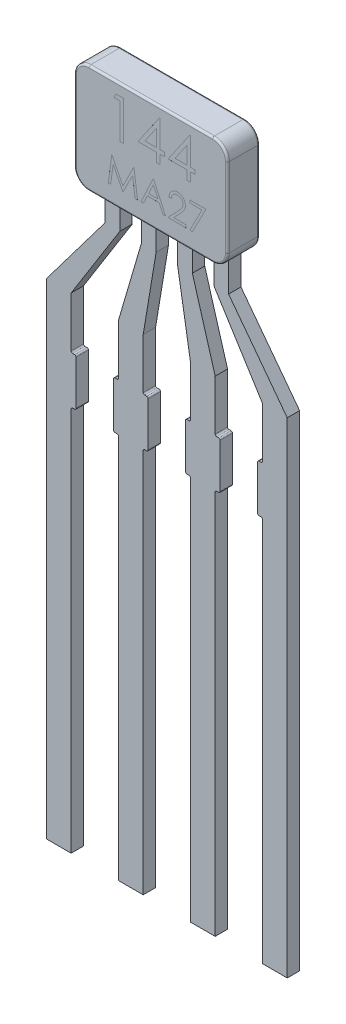
SolidWorks part; units mm, degrees
ref_plane "Front Plane" through (0, 0, 0) normal (0, 0, 1) x (1, 0, 0)
ref_plane "Top Plane" through (0, 0, 0) normal (0, 1, 0) x (1, 0, 0)
ref_plane "Right Plane" through (0, 0, 0) normal (1, 0, 0) x (0, 0, -1)
sketch "Sketch1" plane through (0, 0, 0) normal (0, 0, 1) x (1, 0, 0)
  line L1 (-1.25, 1.1) -> (1.25, 1.1)
  line L2 (-1.55, 0.8) -> (-1.55, -0.8)
  line L3 (-1.25, -1.1) -> (1.25, -1.1)
  line L4 (1.55, 0.8) -> (1.55, -0.8)
  line L5 (-1.55, 1.1) -> (1.55, -1.1) construction
  line L6 (-1.55, -1.1) -> (1.55, 1.1) construction
  arc A0 (-1.55, -0.8) -> (-1.25, -1.1) centre (-1.25, -0.8) ccw
  arc A1 (1.25, -1.1) -> (1.55, -0.8) centre (1.25, -0.8) ccw
  arc A2 (1.55, 0.8) -> (1.25, 1.1) centre (1.25, 0.8) ccw
  arc A3 (-1.25, 1.1) -> (-1.55, 0.8) centre (-1.25, 0.8) ccw
  point P0 (0, 0)
  dimension "D3" = 0.3
  dimension "D1" = 3.1
  dimension "D2" = 2.2
extrude "Boss-Extrude1" add sketch "Sketch1" along normal mid plane 0.65
fillet "Fillet1" radius 0.04 16 edges at (1.4621, -1.0121, -0.325) (0, -1.1, -0.325) (-1.4621, -1.0121, -0.325) (-1.55, 0, -0.325) (-1.4621, 1.0121, -0.325) (0, 1.1, -0.325) (1.4621, 1.0121, -0.325) (1.4621, 1.0121, 0.325) (1.55, 0, 0.325) (1.4621, -1.0121, 0.325) (0, -1.1, 0.325) (-1.4621, -1.0121, 0.325) (-1.55, 0, 0.325) (-1.4621, 1.0121, 0.325) (1.55, 0, -0.325) (0, 1.1, 0.325)
sketch "Sketch2" plane through (0, -1.1, 0) normal (0, -1, 0) x (1, 0, 0)
  line L0 (-1.25, 0.285) -> (-1.25, -0.285) construction
  line L1 (1.25, -0.2484) -> (-1.25, -0.2484)
  line L2 (1.25, -0.2484) -> (1.25, 0.2484)
  line L3 (1.25, 0.2484) -> (-1.25, 0.2484)
  line L4 (-1.25, -0.2484) -> (-1.25, 0.2484)
  line L5 (1.25, -0.2484) -> (-1.25, 0.2484) construction
  line L6 (1.25, 0.2484) -> (-1.25, -0.2484) construction
  point P0 (0, 0)
extrude "Cut-Extrude1" cut sketch "Sketch2" against normal blind 0.4
sketch "Sketch3" plane through (0, 0, -0.2484) normal (0, 0, 1) x (1, 0, 0)
  line L0 (-1.25, -0.7) -> (-1.25, -1.8136)
  line L1 (-1.25, -1.8136) -> (-2.4358, -3.386)
  line L2 (-2.4358, -3.386) -> (-2.4358, -13.2)
  line L3 (1.25, 1.1) -> (-1.25, 1.1) construction
  line L4 (-2.4358, -13.2) -> (-1.9358, -13.2)
  line L5 (-1.9358, -13.2) -> (-1.9358, -5.4173)
  line L6 (-1.9358, -3.386) -> (-0.95, -1.8136)
  line L7 (-0.95, -1.8136) -> (-0.95, -0.7)
  line L8 (-1.25, -0.7) -> (1.25, -0.7) construction
  line L9 (-0.95, -0.7) -> (-1.25, -0.7)
  line L10 (-0.5166, -0.7) -> (-0.5166, -1.8136)
  line L11 (-0.5166, -1.8136) -> (-0.978, -3.386)
  line L12 (-0.978, -3.386) -> (-0.978, -4.4006)
  line L13 (-0.978, -13.2) -> (-0.478, -13.2)
  line L14 (-0.478, -13.2) -> (-0.478, -5.4173)
  line L15 (-0.478, -3.386) -> (-0.2166, -1.8136)
  line L16 (-0.2166, -1.8136) -> (-0.2166, -0.7)
  line L17 (-0.2166, -0.7) -> (-0.5166, -0.7)
  line L18 (0, -0.3575) -> (0, 0.3575) construction
  line L19 (-1.55, 0.8) -> (-1.55, -0.8) construction
  line L20 (-1.9058, -4.4306) -> (-1.8658, -4.4306)
  line L21 (-1.8358, -4.4606) -> (-1.8358, -5.3573)
  line L22 (-1.8658, -5.3873) -> (-1.9058, -5.3873)
  line L23 (-1.008, -4.4306) -> (-1.048, -4.4306)
  line L24 (-1.078, -4.4606) -> (-1.078, -5.3573)
  line L25 (-1.048, -5.3873) -> (-1.008, -5.3873)
  line L26 (-0.448, -4.4306) -> (-0.408, -4.4306)
  line L27 (-0.378, -4.4606) -> (-0.378, -5.3573)
  line L28 (-0.408, -5.3873) -> (-0.448, -5.3873)
  line L29 (-1.9358, -4.4006) -> (-1.9358, -3.386)
  line L30 (-0.978, -5.4173) -> (-0.978, -13.2)
  line L31 (-0.478, -4.4006) -> (-0.478, -3.386)
  arc A0 (-0.478, -4.4006) -> (-0.448, -4.4306) centre (-0.448, -4.4006) ccw
  arc A1 (-0.408, -4.4306) -> (-0.378, -4.4606) centre (-0.408, -4.4606) cw
  arc A2 (-0.378, -5.3573) -> (-0.408, -5.3873) centre (-0.408, -5.3573) cw
  arc A3 (-0.448, -5.3873) -> (-0.478, -5.4173) centre (-0.448, -5.4173) ccw
  arc A4 (-1.008, -5.3873) -> (-0.978, -5.4173) centre (-1.008, -5.4173) cw
  arc A5 (-1.048, -5.3873) -> (-1.078, -5.3573) centre (-1.048, -5.3573) cw
  arc A6 (-0.978, -4.4006) -> (-1.008, -4.4306) centre (-1.008, -4.4006) cw
  arc A7 (-1.048, -4.4306) -> (-1.078, -4.4606) centre (-1.048, -4.4606) ccw
  arc A8 (-1.9058, -5.3873) -> (-1.9358, -5.4173) centre (-1.9058, -5.4173) ccw
  arc A9 (-1.8658, -5.3873) -> (-1.8358, -5.3573) centre (-1.8658, -5.3573) ccw
  arc A10 (-1.8358, -4.4606) -> (-1.8658, -4.4306) centre (-1.8658, -4.4606) ccw
  arc A11 (-1.9058, -4.4306) -> (-1.9358, -4.4006) centre (-1.9058, -4.4006) cw
  point P39 (-0.478, -4.4306)
  point P48 (-0.978, -5.3873)
  point P61 (-1.8358, -4.4306)
  point P64 (-1.9358, -4.4306)
  dimension "D8" = 0.03
  dimension "D1" = 14.3
  dimension "D2" = 0.5
  dimension "D3" = 0.3
  dimension "D4" = 0.2166
  dimension "D5" = 0.8858
  dimension "D6" = 0.478
  dimension "D7" = 0.1
extrude "Boss-Extrude2" add sketch "Sketch3" along normal blind 0.25
mirror "Mirror1" about plane through (0, 0, 0) normal (1, 0, 0) of "Boss-Extrude2"
sketch "Sketch4" plane through (0, 0, 0.325) normal (0, 0, 1) x (1, 0, 0)
  text T0 "144\r\n" font "Century Gothic" height in points 3
  text T1 "MA27" font "Century Gothic" height in points 2
extrude "Cut-Extrude2" cut sketch "Sketch4" against normal blind 0.0001
